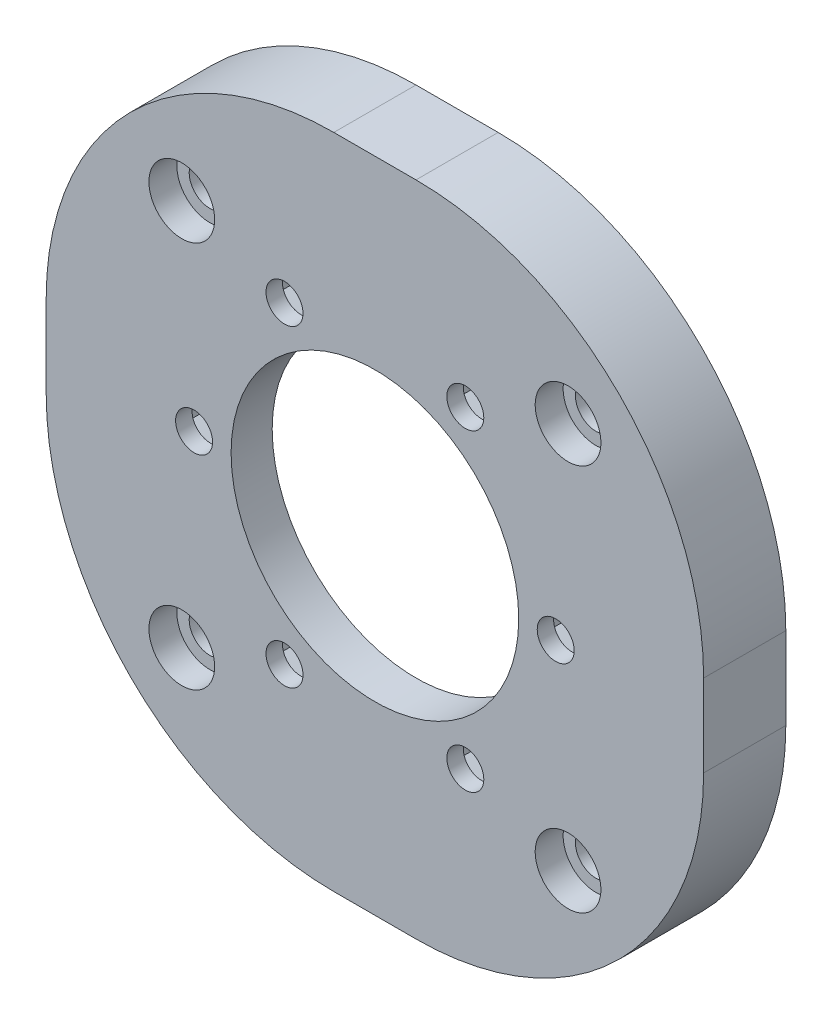
SolidWorks part; units mm, degrees
ref_plane "Plan de face" through (0, 0, 0) normal (0, 0, 1) x (1, 0, 0)
ref_plane "Plan de dessus" through (0, 0, 0) normal (0, 1, 0) x (1, 0, 0)
ref_plane "Plan de droite" through (0, 0, 0) normal (1, 0, 0) x (0, 0, -1)
sketch "Esquisse1" plane through (0, 0, 0) normal (0, 0, 1) x (1, 0, 0)
  line L0 (0, 0) -> (22, 0) construction
  line L1 (0, 0) -> (11, -19.0526) construction
  line L2 (0, 0) -> (-11, -19.0526) construction
  line L3 (0, 0) -> (-22, 0) construction
  line L4 (0, 0) -> (-11, 19.0526) construction
  line L5 (0, 0) -> (11, 19.0526) construction
  line L6 (-23.5, 21.05) -> (-23.5, 23.55)
  line L7 (23.5, -23.55) -> (21, -23.55)
  line L8 (23.5, -23.55) -> (23.5, -21.05)
  line L9 (23.5, 23.55) -> (21, 23.55)
  line L10 (-23.5, -23.55) -> (-23.5, -21.05)
  line L11 (23.5, -23.55) -> (-23.5, 23.55) construction
  line L12 (23.5, 23.55) -> (-23.5, -23.55) construction
  line L13 (-21, 23.55) -> (-23.5, 23.55)
  line L14 (23.5, 21.05) -> (23.5, 23.55)
  line L15 (-21, -23.55) -> (-23.5, -23.55)
  line L17 (5, -40) -> (-5, -40)
  line L18 (40, -5) -> (40, 5)
  line L19 (5, 40) -> (-5, 40)
  line L20 (-40, -5) -> (-40, 5)
  line L21 (40, -40) -> (-40, 40) construction
  line L22 (40, 40) -> (-40, -40) construction
  circle A0 centre (22, 0) radius 2.25
  circle A1 centre (11, -19.0526) radius 2.25
  circle A2 centre (-11, -19.0526) radius 2.25
  circle A3 centre (-22, 0) radius 2.25
  circle A4 centre (-11, 19.0526) radius 2.25
  circle A5 centre (11, 19.0526) radius 2.25
  circle A6 centre (-23.5, 23.55) radius 2.5
  circle A7 centre (23.5, 23.55) radius 2.5
  circle A8 centre (23.5, -23.55) radius 2.5
  circle A9 centre (-23.5, -23.55) radius 2.5
  circle A11 centre (0, 0) radius 17.5
  arc A12 (-5, -40) -> (-40, -5) centre (-5, -5) cw
  arc A13 (5, -40) -> (40, -5) centre (5, -5) ccw
  arc A14 (40, 5) -> (5, 40) centre (5, 5) ccw
  arc A15 (-5, 40) -> (-40, 5) centre (-5, 5) ccw
  point P17 (0, 0)
  dimension "D5" = 4.5
  dimension "D6" = 5
  dimension "D7" = 5
  dimension "D8" = 5
  dimension "D9" = 5
  dimension "D10" = 35
  dimension "D11" = 35
  dimension "D1" = 22
  dimension "D3" = 47
  dimension "D4" = 47.1
  dimension "D12" = 80
  dimension "D13" = 80
  dimension "D2" = 6
extrude "Boss.-Extru.1" add sketch "Esquisse1" along normal blind 10
sketch "Esquisse2" plane through (0, 0, 0) normal (0, 0, -1) x (-1, 0, 0)
  line L1 (28.5, -28.5) -> (-28.5, -28.5)
  line L2 (28.5, -28.5) -> (28.5, 28.5)
  line L3 (28.5, 28.5) -> (-28.5, 28.5)
  line L4 (-28.5, -28.5) -> (-28.5, 28.5)
  line L5 (28.5, -28.5) -> (-28.5, 28.5) construction
  line L6 (28.5, 28.5) -> (-28.5, -28.5) construction
  point P0 (0, 0)
  dimension "D1" = 57
  dimension "D2" = 57
extrude "Enlèv. mat.-Extru.2" cut sketch "Esquisse2" against normal blind 5
sketch "Esquisse4" plane through (0, 0, 5) normal (0, 0, -1) x (-1, 0, 0)
  line L0 (-11, 19.0526) -> (-7.4965, 21.0672) construction
  line L1 (-7.4965, 21.0672) -> (-10.993, 23.094)
  line L2 (-10.993, 23.094) -> (-14.4965, 21.0794)
  line L3 (-14.4965, 21.0794) -> (-14.5035, 17.0379)
  line L4 (-14.5035, 17.0379) -> (-11.007, 15.0111)
  line L5 (-11.007, 15.0111) -> (-7.5035, 17.0258)
  line L6 (-7.5035, 17.0258) -> (-7.4965, 21.0672)
  line L7 (-11, 19.0526) -> (-7.5, 19.0465) construction
  line L8 (14.4965, 17.0258) -> (14.5035, 21.0672)
  line L9 (14.5035, 21.0672) -> (11.007, 23.094)
  line L10 (11.007, 23.094) -> (7.5035, 21.0794)
  line L11 (7.5035, 21.0794) -> (7.4965, 17.0379)
  line L12 (7.4965, 17.0379) -> (10.993, 15.0111)
  line L13 (10.993, 15.0111) -> (14.4965, 17.0258)
  line L14 (21.993, -4.0415) -> (25.4965, -2.0268)
  line L15 (25.4965, -2.0268) -> (25.5035, 2.0146)
  line L16 (25.5035, 2.0146) -> (22.007, 4.0415)
  line L17 (22.007, 4.0415) -> (18.5035, 2.0268)
  line L18 (18.5035, 2.0268) -> (18.4965, -2.0146)
  line L19 (18.4965, -2.0146) -> (21.993, -4.0415)
  line L20 (7.4965, -21.0672) -> (10.993, -23.094)
  line L21 (10.993, -23.094) -> (14.4965, -21.0794)
  line L22 (14.4965, -21.0794) -> (14.5035, -17.0379)
  line L23 (14.5035, -17.0379) -> (11.007, -15.0111)
  line L24 (11.007, -15.0111) -> (7.5035, -17.0258)
  line L25 (7.5035, -17.0258) -> (7.4965, -21.0672)
  line L26 (-14.4965, -17.0258) -> (-14.5035, -21.0672)
  line L27 (-14.5035, -21.0672) -> (-11.007, -23.094)
  line L28 (-11.007, -23.094) -> (-7.5035, -21.0794)
  line L29 (-7.5035, -21.0794) -> (-7.4965, -17.0379)
  line L30 (-7.4965, -17.0379) -> (-10.993, -15.0111)
  line L31 (-10.993, -15.0111) -> (-14.4965, -17.0258)
  line L32 (-21.993, 4.0415) -> (-25.4965, 2.0268)
  line L33 (-25.4965, 2.0268) -> (-25.5035, -2.0146)
  line L34 (-25.5035, -2.0146) -> (-22.007, -4.0415)
  line L35 (-22.007, -4.0415) -> (-18.5035, -2.0268)
  line L36 (-18.5035, -2.0268) -> (-18.4965, 2.0146)
  line L37 (-18.4965, 2.0146) -> (-21.993, 4.0415)
  circle A0 centre (-11, 19.0526) radius 3.5 construction
  point P42 (0, 0)
  dimension "D1" = 30
  dimension "D2" = 3.5
extrude "Enlèv. mat.-Extru.3" cut sketch "Esquisse4" against normal blind 3
sketch "Esquisse5" plane through (0, 0, 10) normal (0, 0, 1) x (1, 0, 0)
  line L0 (0, 0) -> (0, 9.9715) construction
  circle A0 centre (-23.5, 23.55) radius 4
  circle A1 centre (-23.5, -23.55) radius 4
  circle A2 centre (23.5, 23.55) radius 4
  circle A3 centre (23.5, -23.55) radius 4
  dimension "D1" = 8
  dimension "D2" = 8
extrude "Enlèv. mat.-Extru.4" cut sketch "Esquisse5" against normal blind 3.4
